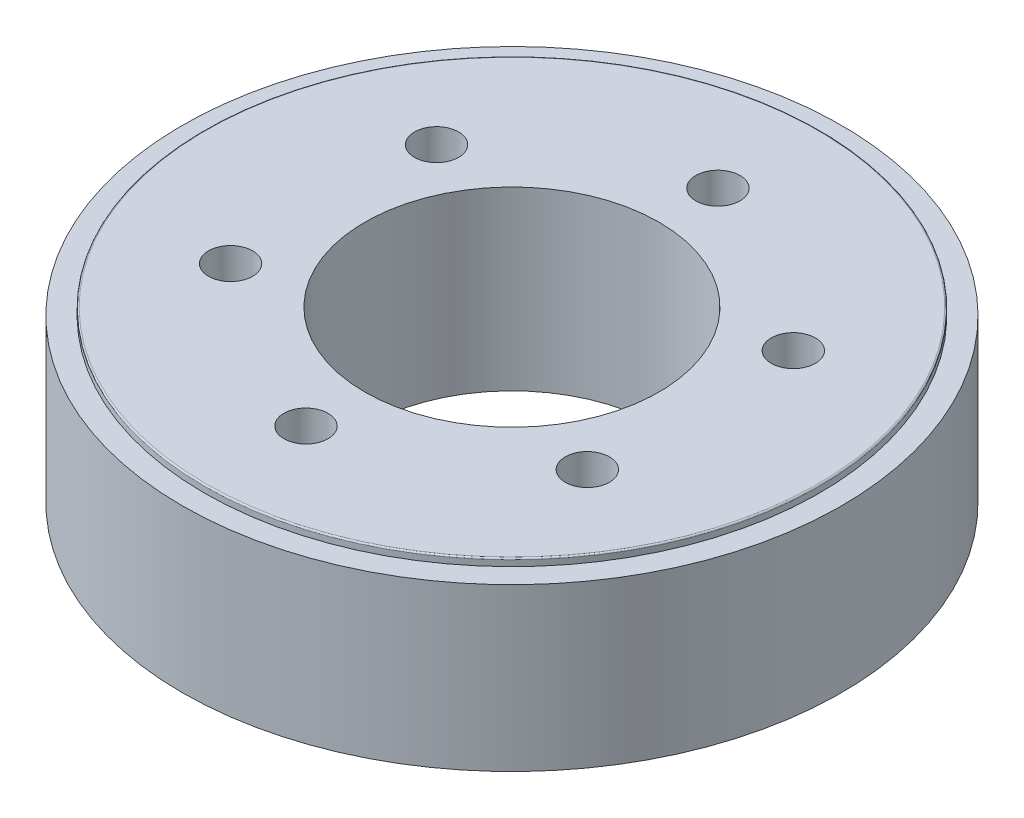
SolidWorks part; units mm, degrees
material "Plain Carbon Steel"
ref_plane "Front Plane" through (0, 0, 0) normal (0, 0, 1) x (1, 0, 0)
ref_plane "Top Plane" through (0, 0, 0) normal (0, 1, 0) x (1, 0, 0)
ref_plane "Right Plane" through (0, 0, 0) normal (1, 0, 0) x (0, 0, -1)
sketch "Sketch1" plane through (0, 0, 0) normal (0, 1, 0) x (1, 0, 0)
  circle A0 centre (0, 0) radius 10
  circle A4 centre (0, 0) radius 22.4
  dimension "D1" = 44.8
  dimension "D2" = 20
extrude "Boss-Extrude1" add sketch "Sketch1" along normal blind 12
sketch "Sketch2" plane through (0, 12, 0) normal (0, 1, 0) x (1, 0, 0)
  circle A0 centre (0, 0) radius 20.9
  circle A1 centre (0, 0) radius 22.4
  dimension "D1" = 41.8
extrude "Cut-Extrude1" cut sketch "Sketch2" against normal blind 0.5
fillet "Fillet1" radius 0.1 1 edges at (0, 12, 20.9)
ref_plane "Plane1" through (0, 6, 0) normal (0, 1, 0) x (1, 0, 0)
mirror "Mirror3" about plane through (0, 6, 0) normal (0, 1, 0) of "Cut-Extrude1"
fillet "Fillet2" radius 0.1 1 edges at (0, 0, 20.9)
sketch "Sketch3" plane through (0, 12, 0) normal (0, 1, 0) x (1, 0, 0)
  circle A0 centre (0, 0) radius 14
  circle A1 centre (0, 14) radius 1.5
  circle A2 centre (12.1244, 7) radius 1.5
  circle A3 centre (12.1244, -7) radius 1.5
  circle A4 centre (0, -14) radius 1.5
  circle A5 centre (-12.1244, -7) radius 1.5
  circle A6 centre (-12.1244, 7) radius 1.5
  point P17 (0, 0)
  dimension "D1" = 28
  dimension "D2" = 3
  dimension "D3" = 6
extrude "Cut-Extrude2" cut sketch "Sketch3" against normal up to surface (12 mm away) contours A1 | A6 | A5 | A4 | A3 | A2 up to face at (0, 0, 20.8)
